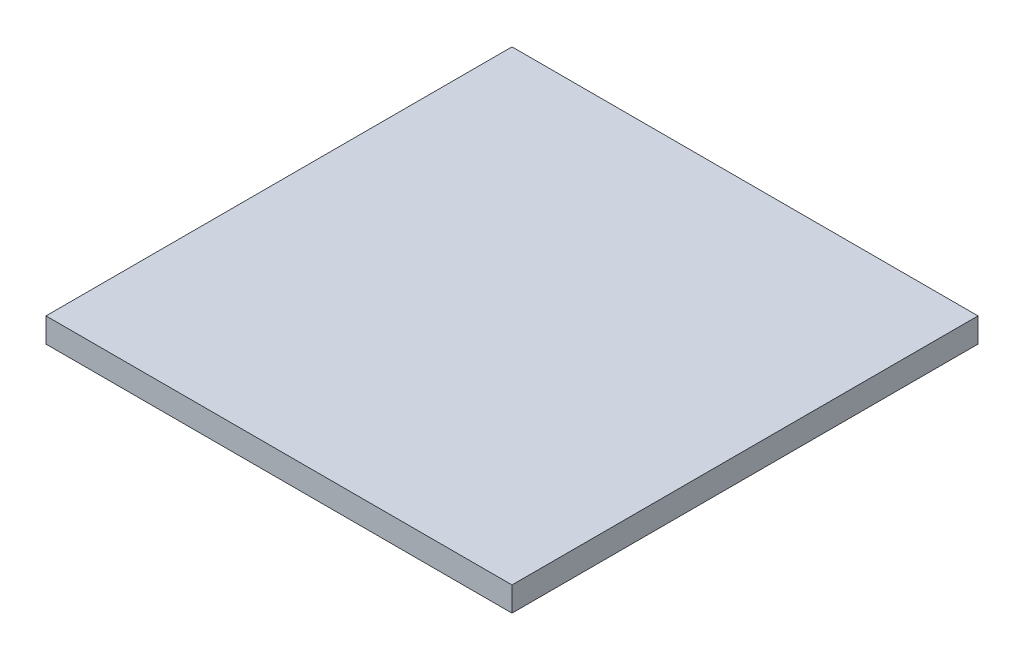
SolidWorks part; units mm, degrees
ref_plane "Front Plane" through (0, 0, 0) normal (0, 0, 1) x (1, 0, 0)
ref_plane "Top Plane" through (0, 0, 0) normal (0, 1, 0) x (1, 0, 0)
ref_plane "Right Plane" through (0, 0, 0) normal (1, 0, 0) x (0, 0, -1)
other "Configuration Table"
sketch "Sketch1" plane through (0, 0, 0) normal (0, 0, 1) x (1, 0, 0)
  line L1 (400, 1958) -> (600, 1958)
  line L2 (400, 1958) -> (400, 1968.5)
  line L3 (400, 1968.5) -> (600, 1968.5)
  line L4 (600, 1958) -> (600, 1968.5)
extrude "OVEN_egzoz_izgarasi_ust_1" add sketch "Sketch1" against normal blind 200 from offset 300 separate body
